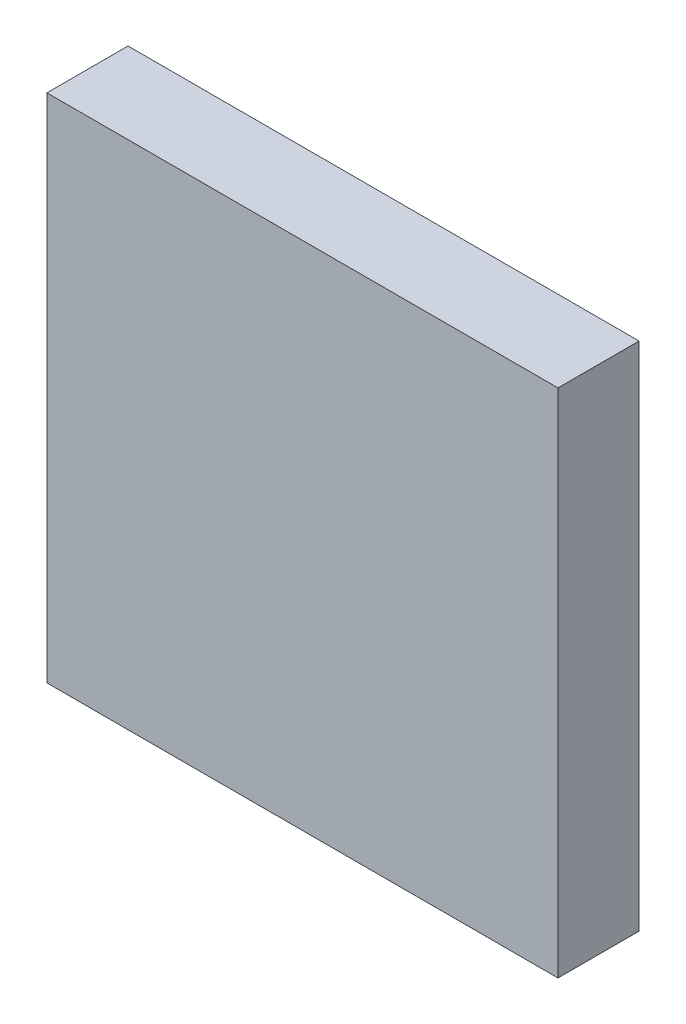
SolidWorks part; units mm, degrees
ref_plane "Front Plane" through (0, 0, 0) normal (0, 0, 1) x (1, 0, 0)
ref_plane "Top Plane" through (0, 0, 0) normal (0, 1, 0) x (1, 0, 0)
ref_plane "Right Plane" through (0, 0, 0) normal (1, 0, 0) x (0, 0, -1)
sketch "Sketch1" plane through (0, 0, 0) normal (0, 0, 1) x (1, 0, 0)
  line L1 (0, 0) -> (20, 0)
  line L2 (0, 0) -> (0, 20)
  line L3 (0, 20) -> (20, 20)
  line L4 (20, 0) -> (20, 20)
  dimension "D1" = 20
  dimension "D2" = 20
extrude "Boss-Extrude1" add sketch "Sketch1" along normal blind 3.175
